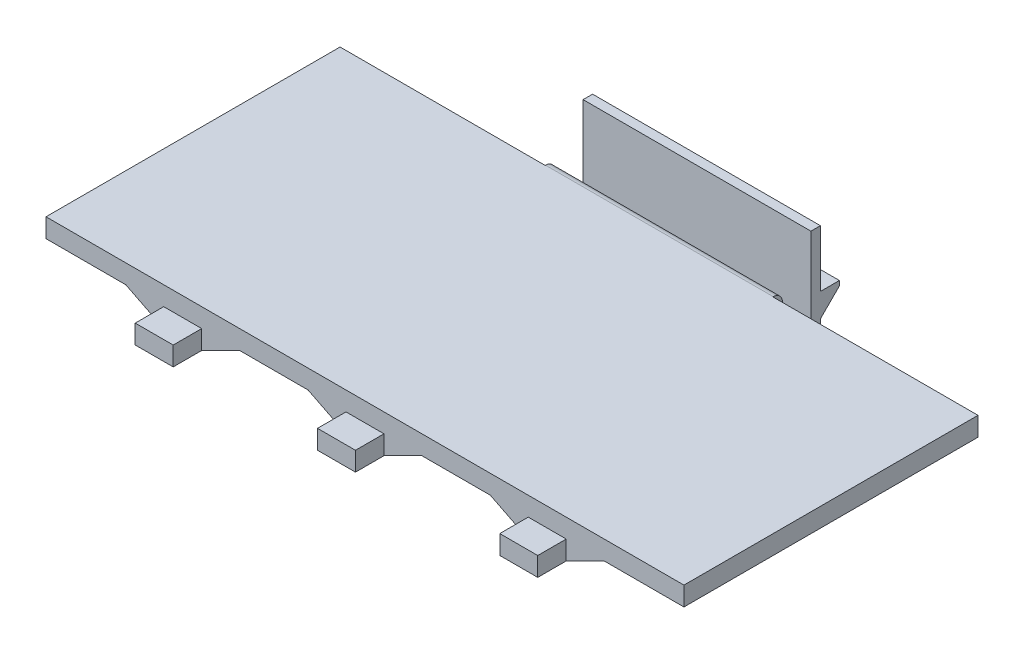
SolidWorks part; units mm, degrees
ref_plane "Front Plane" through (0, 0, 0) normal (0, 0, 1) x (1, 0, 0)
ref_plane "Top Plane" through (0, 0, 0) normal (0, 1, 0) x (1, 0, 0)
ref_plane "Right Plane" through (0, 0, 0) normal (1, 0, 0) x (0, 0, -1)
sketch "Sketch1" plane through (0, 0, 0) normal (0, 1, 0) x (1, 0, 0)
  line L1 (0, 0) -> (53.34, 0)
  line L2 (0, 0) -> (0, 24.5872)
  line L3 (0, 24.5872) -> (53.34, 24.5872)
  line L4 (53.34, 0) -> (53.34, 24.5872)
  dimension "D1" = 24.5872
  dimension "D2" = 53.34
extrude "Boss-Extrude1" add sketch "Sketch1" along normal blind 1.5875
sketch "Sketch2" plane through (0, 0, 0) normal (0, -1, 0) x (1, 0, 0)
  line L0 (0, 0) -> (53.34, 0) construction
  line L1 (0, 0) -> (53.34, 0)
  line L2 (40.3225, 0) -> (40.3225, 2.3813)
  line L3 (25.0825, 0) -> (28.2575, 0)
  line L4 (25.0825, 0) -> (25.0825, 2.3813)
  line L5 (25.0825, 2.3813) -> (28.2575, 2.3813)
  line L6 (28.2575, 0) -> (28.2575, 2.3813)
  line L7 (40.3225, 0) -> (43.4975, 0)
  line L8 (43.4975, 0) -> (43.4975, 2.3813)
  line L9 (40.3225, 2.3813) -> (43.4975, 2.3813)
  line L10 (9.8425, 0) -> (9.8425, 2.3812)
  line L11 (9.8425, 0) -> (13.0175, 0)
  line L12 (13.0175, 0) -> (13.0175, 2.3812)
  line L13 (9.8425, 2.3812) -> (13.0175, 2.3812)
  point P6 (26.67, 2.3813)
  point P7 (26.67, 0)
  line M11 (53.34, 0) -> (0, 0)
  dimension "D1" = 2.3813
  dimension "D2" = 3.175
  dimension "D4" = 15.24
  dimension "D6" = 15.24
  dimension "D3" = 2
  dimension "D5" = 2
extrude "Boss-Extrude2" add sketch "Sketch2" along normal blind 1.5875 separate body contours L13 L10 L12 M11 | L6 L5 L4 M11 | L9 L2 L1 L8
sketch "Sketch4" plane through (0, -1.5875, 0) normal (0, -1, 0) x (1, 0, 0)
  line L1 (43.4975, 0) -> (40.3225, 0)
  line L2 (43.4975, 0) -> (43.4975, -3.175)
  line L3 (43.4975, -3.175) -> (40.3225, -3.175)
  line L4 (40.3225, 0) -> (40.3225, -3.175)
  line L5 (40.3225, 0) -> (40.3225, 2.3813) construction
  dimension "D1" = 3.175
sketch "Sketch5" plane through (0, 0, 0) normal (0, -1, 0) x (1, 0, 0)
  line L0 (0, 0) -> (53.34, 0) construction
  line L1 (37.1475, 0) -> (46.6725, 0)
  line L2 (37.1475, 0) -> (37.1475, -6.35)
  line L3 (37.1475, -6.35) -> (46.6725, -6.35)
  line L4 (46.6725, 0) -> (46.6725, -6.35)
  line L5 (40.3225, 0) -> (40.3225, -3.175) construction
  line L6 (43.4975, 0) -> (43.4975, -3.175) construction
  line L7 (43.4975, -3.175) -> (40.3225, -3.175) construction
  dimension "D1" = 3.175
  dimension "D2" = 3.175
  dimension "D3" = 3.175
loft "Loft2" add profiles "Sketch5", "Sketch4"
pattern_linear "LPattern1" count 3 spacing 15.24 along (-1, 0, 0) of "Loft2"
ref_plane "Plane1" through (26.67, 0, 0) normal (-1, 0, 0) x (0, 0, 1)
sketch "Sketch7" plane through (26.67, 0, 0) normal (-1, 0, 0) x (0, 0, 1)
  line L0 (-30.1434, -0.3969) -> (-28.5559, -1.9844)
  line L1 (-24.5872, 1.5875) -> (-25.3809, 1.5875)
  line L2 (-24.5872, 1.5875) -> (-24.5872, -4.7625)
  line L3 (-24.5872, -4.7625) -> (-26.2125, -4.7625)
  line L4 (-25.3809, 1.5875) -> (-25.3809, -3.9687)
  line L5 (-26.2125, -4.7625) -> (-28.5559, -4.7625)
  line L7 (-25.3809, -3.9687) -> (-27.7622, -3.9688)
  line L11 (-28.5559, 4.7625) -> (-27.7622, 4.7625)
  line L12 (-27.7622, -3.9688) -> (-27.7622, 4.7625)
  line L13 (-28.5559, 0) -> (-30.1434, 0)
  line L16 (-30.1434, 0) -> (-30.1434, -0.3969)
  line L17 (0, 0) -> (-24.5872, 0) construction
  line L18 (0, 0) -> (-24.5872, 0)
  line L19 (-28.5559, 4.7625) -> (-28.5559, 0)
  line L20 (-28.5559, -1.9844) -> (-28.5559, -4.7625)
  dimension "D1" = 6.35
  dimension "D2" = 0.7937
  dimension "D3" = 0.7937
  dimension "D4" = 2.3813
  dimension "D5" = 9.525
  dimension "D6" = 0.7937
  dimension "D7" = 0.7937
  dimension "D8" = 1.5875
  dimension "D9" = 135
  dimension "D10" = 0.3969
extrude "Boss-Extrude3" add sketch "Sketch7" along normal blind 9.525 and the other way blind 9.525 contours L0 L20 L5 L3 L2 L1 L4 L7 L12 L11 L19 L13 L16
fillet "Fillet1" radius 0.762 5 edges at (26.67, 1.5875, -25.3809) (26.67, -4.7625, -24.5872) (26.67, -4.7625, -28.5559) (26.67, -3.9687, -25.3809) (26.67, -3.9688, -27.7622)
